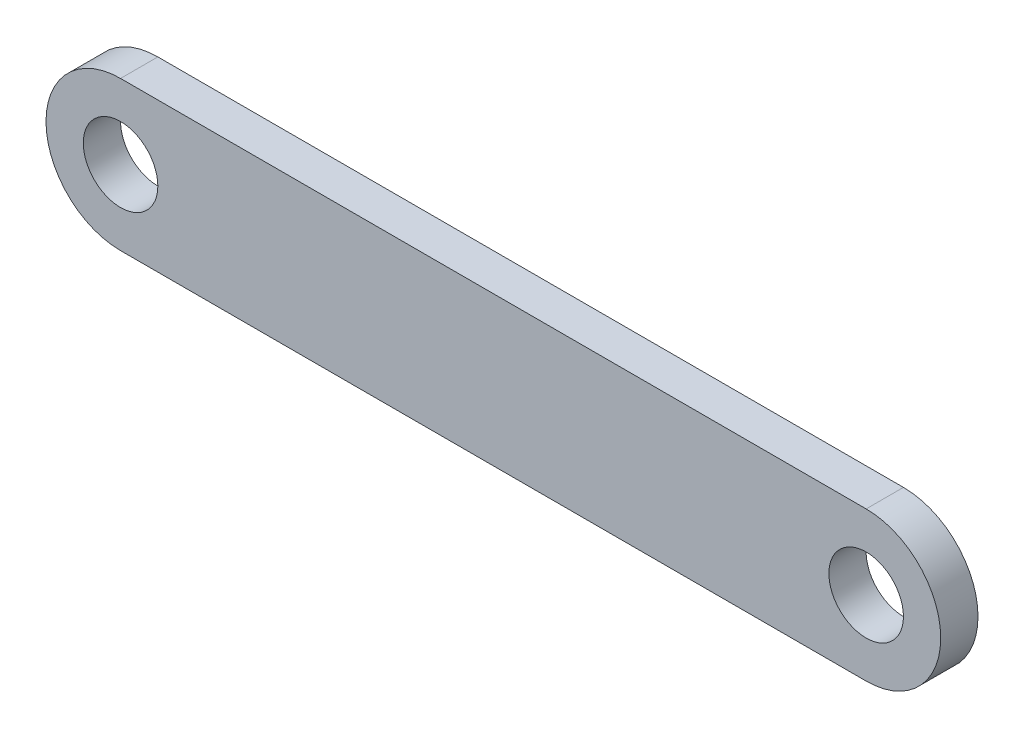
SolidWorks part; units mm, degrees
ref_plane "Front Plane" through (0, 0, 0) normal (0, 0, 1) x (1, 0, 0)
ref_plane "Top Plane" through (0, 0, 0) normal (0, 1, 0) x (1, 0, 0)
ref_plane "Right Plane" through (0, 0, 0) normal (1, 0, 0) x (0, 0, -1)
sketch "Sketch3" plane through (0, 0, 0) normal (0, 0, 1) x (1, 0, 0)
  line L0 (50, 0) -> (-50, 0) construction
  line L1 (50, -10) -> (-50, -10)
  line L2 (50, 10) -> (-50, 10)
  arc A0 (50, -10) -> (50, 10) centre (50, 0) ccw
  arc A1 (-50, 10) -> (-50, -10) centre (-50, 0) ccw
  circle A2 centre (-50, 0) radius 5
  circle A3 centre (50, 0) radius 5
  point P2 (0, 0)
  dimension "D1" = 20
  dimension "D2" = 100
extrude "Boss-Extrude1" add sketch "Sketch3" along normal blind 5
